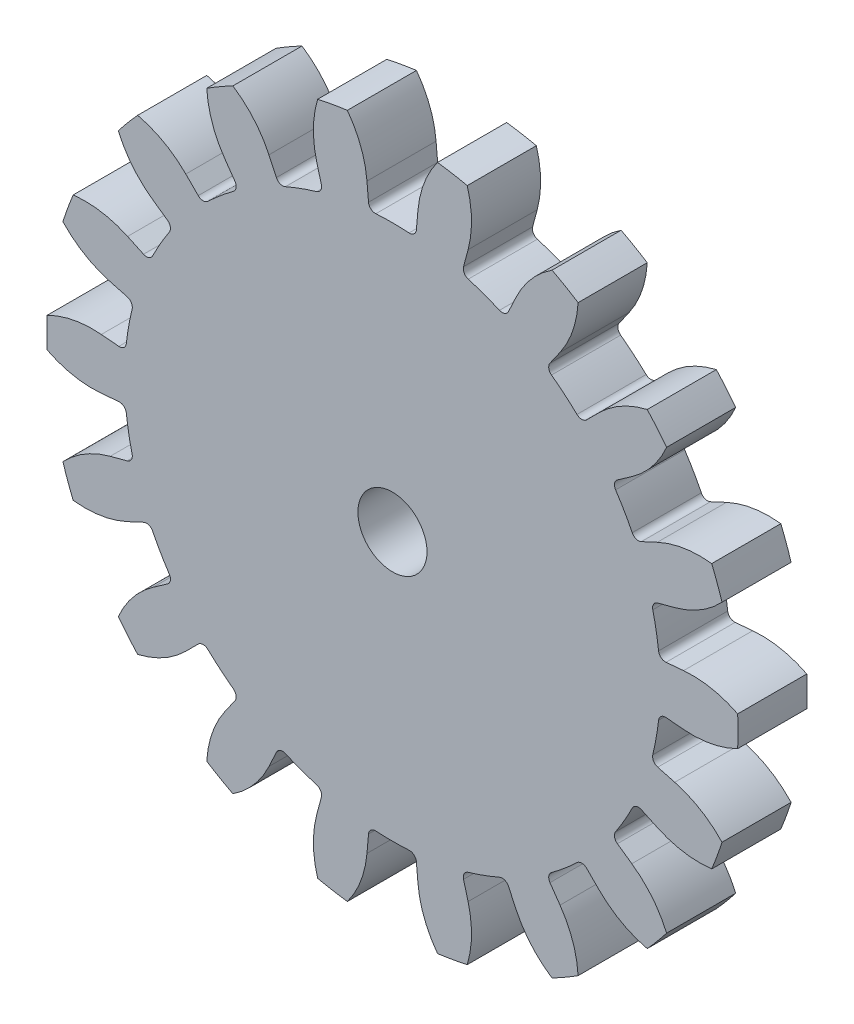
SolidWorks part; units mm, degrees
ref_plane "Front Plane" through (0, 0, 0) normal (0, 0, 1) x (1, 0, 0)
ref_plane "Top Plane" through (0, 0, 0) normal (0, 1, 0) x (1, 0, 0)
ref_plane "Right Plane" through (0, 0, 0) normal (1, 0, 0) x (0, 0, -1)
sketch "Sketch1" plane through (0, 0, 0) normal (0, 0, 1) x (1, 0, 0)
  line L0 (0, 0) -> (78.4991, 0) construction
  line L1 (4.924, 0.8682) -> (38.1613, 6.7289)
  line L2 (0, 0) -> (54.2811, 4.749) construction
  line L3 (0, 0) -> (56.5872, 2.4707) construction
  line L4 (42.1241, 3.6854) -> (38.6025, 3.3773)
  line L5 (42.1241, -3.6854) -> (38.6025, -3.3773)
  line L6 (4.924, -0.8682) -> (38.1613, -6.7289)
  circle A0 centre (0, 0) radius 42.285 construction
  circle A1 centre (0, 0) radius 50 construction
  circle A2 centre (0, 0) radius 38.75 construction
  arc A3 (42.1241, 3.6854) -> (49.9524, 2.181) centre (43.3938, -10.8274) cw
  arc A4 (38.1613, 6.7289) -> (38.6025, 3.3773) centre (0, 0) cw
  arc A5 (49.9524, -2.181) -> (49.9524, 2.181) centre (0, 0) ccw
  arc A6 (42.1241, -3.6854) -> (49.9524, -2.181) centre (43.3938, 10.8274) ccw
  arc A7 (38.1613, -6.7289) -> (38.6025, -3.3773) centre (0, 0) ccw
  arc A8 (4.924, -0.8682) -> (4.924, 0.8682) centre (0, 0) ccw
  dimension "D1" = 100
  dimension "D2" = 84.57
  dimension "D3" = 11.25
  dimension "D10" = 5
  dimension "D4" = 10
  dimension "D5" = 5
  dimension "D6" = 2.5
  dimension "D7" = 78.4991
  dimension "D8" = 56.5872
  dimension "D9" = 54.2811
extrude "Boss-Extrude1" add sketch "Sketch1" along normal blind 10
fillet "Fillet1" radius 1 2 edges at (38.6025, -3.3773, 5) (38.6025, 3.3773, 5)
pattern_circular "CirPattern2" count 18 over 360 about axis through (0, 0, 0) along (0, 0, 1) of "Boss-Extrude1", "Fillet1"
